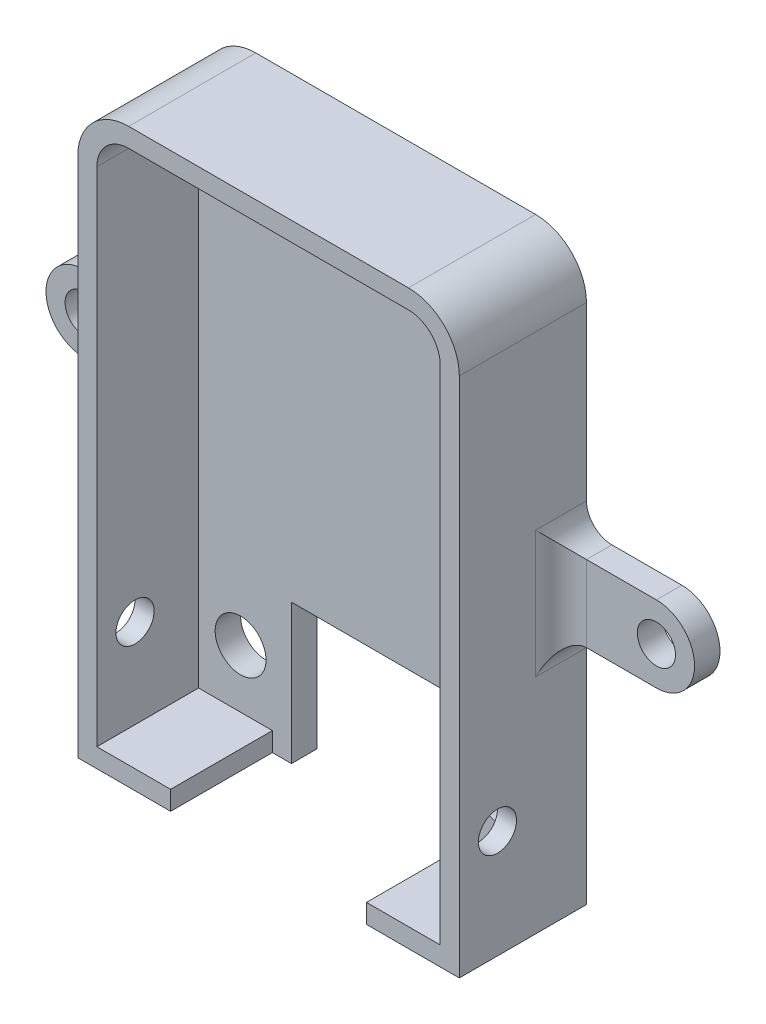
SolidWorks part; units mm, degrees
ref_plane "Plan de face" through (0, 0, 0) normal (0, 0, 1) x (1, 0, 0)
ref_plane "Plan de dessus" through (0, 0, 0) normal (0, 1, 0) x (1, 0, 0)
ref_plane "Plan de droite" through (0, 0, 0) normal (1, 0, 0) x (0, 0, -1)
sketch "Esquisse1" plane through (0, 0, 0) normal (0, 0, 1) x (1, 0, 0)
  line L1 (-15, 22.5) -> (15, 22.5)
  line L2 (-15, 22.5) -> (-15, -22.5)
  line L3 (-15, -22.5) -> (15, -22.5)
  line L4 (15, 22.5) -> (15, -22.5)
  line L5 (-15, 22.5) -> (15, -22.5) construction
  line L6 (-15, -22.5) -> (15, 22.5) construction
  point P0 (0, 0)
  dimension "D1" = 45
  dimension "D2" = 30
extrude "Boss.-Extru.1" add sketch "Esquisse1" along normal blind 2
sketch "Esquisse3" plane through (0, 0, 0) normal (0, 0, 1) x (1, 0, 0)
  line L0 (15, -22.5) -> (15, 22.5) construction
  line L1 (15, 22.5) -> (-15, 22.5) construction
  line L2 (0, -27.082) -> (0, 31.3004) construction
  line L3 (22.6204, 0) -> (-27.0667, 0) construction
  line L5 (6.2, -22.5) -> (-6.2, -22.5)
  line L6 (-15, -22.5) -> (15, -22.5) construction
  line L7 (-6.2, -22.5) -> (-6.2, -11.5)
  line L8 (-6.2, -11.5) -> (6.2, -11.5)
  line L9 (6.2, -22.5) -> (6.2, -11.5)
  circle A0 centre (10.2, 16.45) radius 2
  circle A1 centre (-10.2, 16.45) radius 2
  circle A2 centre (-10.2, -16.45) radius 2
  circle A3 centre (10.2, -16.45) radius 2
  point P23 (-6.2, -22.5)
  point P25 (0, -11.5)
  point P26 (0, -22.5)
  dimension "D3" = 4
  dimension "D4" = 4
  dimension "D1" = 4.8
  dimension "D2" = 6.05
  dimension "D5" = 11
extrude "Enlèv. mat.-Extru.1" cut sketch "Esquisse3" along normal through all
fillet "Congé1" radius 4 2 edges at (15, 22.5, 1) (-15, 22.5, 1)
sketch "Esquisse6" plane through (0, 0, 0) normal (0, 0, 1) x (1, 0, 0)
  line L0 (7.7, -21) -> (7.7, -22.5)
  line L1 (-7.7, -21) -> (-7.7, -22.5)
  line L16 (13.5, -21) -> (13.5, 18.5)
  line L17 (11, 21) -> (-11, 21)
  line L18 (-13.5, 18.5) -> (-13.5, -21)
  line L19 (-13.5, -21) -> (-7.7, -21)
  line L20 (-7.7, -21) -> (-7.7, -10)
  line L21 (-7.7, -10) -> (7.7, -10)
  line L22 (7.7, -10) -> (7.7, -21)
  line L23 (7.7, -21) -> (13.5, -21)
  line L24 (13.5, -21) -> (13.5, 18.5)
  line L25 (11, 21) -> (-11, 21)
  line L26 (-13.5, 18.5) -> (-13.5, -21)
  line L27 (-13.5, -21) -> (-7.7, -21)
  line L31 (7.7, -21) -> (13.5, -21)
  line L32 (15, -22.5) -> (15, 18.5)
  line L33 (11, 22.5) -> (-11, 22.5)
  line L34 (-15, 18.5) -> (-15, -22.5)
  line L35 (-15, -22.5) -> (-6.2, -22.5)
  line L36 (-6.2, -22.5) -> (-6.2, -11.5)
  line L37 (-6.2, -11.5) -> (6.2, -11.5)
  line L38 (6.2, -11.5) -> (6.2, -22.5)
  line L39 (6.2, -22.5) -> (15, -22.5)
  line L40 (15, -22.5) -> (15, 18.5)
  line L41 (11, 22.5) -> (-11, 22.5)
  line L42 (-15, 18.5) -> (-15, -22.5)
  line L43 (-15, -22.5) -> (-7.7, -22.5)
  line L47 (7.7, -22.5) -> (15, -22.5)
  arc A4 (13.5, 18.5) -> (11, 21) centre (11, 18.5) ccw
  arc A5 (-11, 21) -> (-13.5, 18.5) centre (-11, 18.5) ccw
  arc A6 (13.5, 18.5) -> (11, 21) centre (11, 18.5) ccw
  arc A7 (-11, 21) -> (-13.5, 18.5) centre (-11, 18.5) ccw
  arc A8 (15, 18.5) -> (11, 22.5) centre (11, 18.5) ccw
  arc A9 (-11, 22.5) -> (-15, 18.5) centre (-11, 18.5) ccw
  arc A10 (15, 18.5) -> (11, 22.5) centre (11, 18.5) ccw
  arc A11 (-11, 22.5) -> (-15, 18.5) centre (-11, 18.5) ccw
  dimension "D1" = 1.5
  dimension "D2" = 0
extrude "Boss.-Extru.2" add sketch "Esquisse6" along normal blind 10
sketch "Esquisse7" plane through (0, 0, 0) normal (1, 0, 0) x (0, 0, -1)
  line L0 (-10, -22.5) -> (-10, 18.5) construction
  line L1 (-10, -22.5) -> (0, -22.5) construction
  circle A0 centre (-7, -14) radius 1.5
  dimension "D1" = 3
  dimension "D2" = 3
  dimension "D3" = 8.5
extrude "Enlèv. mat.-Extru.2" cut sketch "Esquisse7" against normal through all both and the other way through all
sketch "Esquisse10" plane through (0, 0, 0) normal (0, 0, 1) x (1, 0, 0)
  line L0 (27.8968, 0) -> (-20.5123, 0) construction
  line L2 (15, -22.5) -> (15, 18.5) construction
  line L3 (15, 3) -> (22.5, 3)
  line L4 (22.5, -3) -> (15, -3)
  line L5 (15, -3) -> (15, 3)
  arc A0 (22.5, 3) -> (22.5, -3) centre (22.5, 0) cw
  circle A1 centre (22.5, 0) radius 1.5
  point P3 (15, 0)
  dimension "D2" = 3
  dimension "D3" = 3
  dimension "D1" = 7.5
extrude "Boss.-Extru.3" add sketch "Esquisse10" along normal blind 2
fillet "Congé2" radius 2 3 edges at (15, 3, 1) (15, -3, 1) (15, 0, 2)
mirror "Symétrie2" about plane through (0, 0, 0) normal (1, 0, 0) of "Boss.-Extru.3"
fillet "Congé3" radius 2 3 edges at (-15, 3, 1) (-15, -3, 1) (-15, 0, 2)
